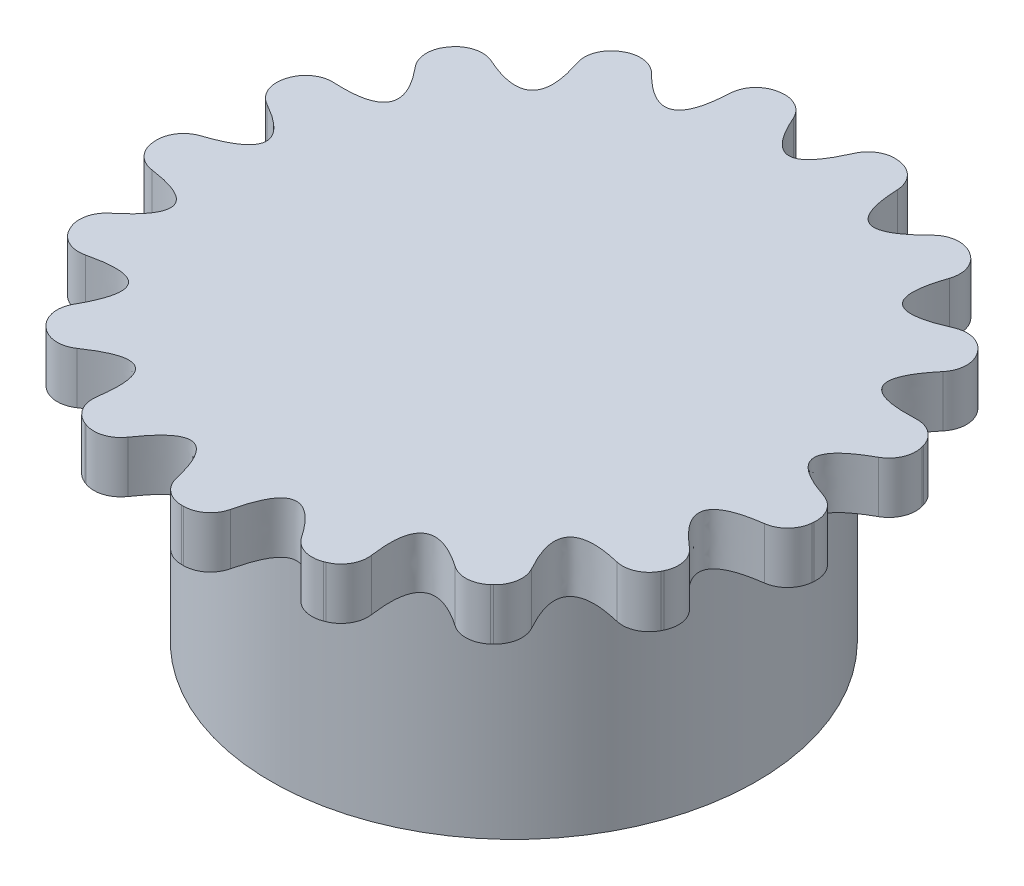
SolidWorks part; units mm, degrees
material "1023 Carbon Steel Sheet (SS)"
ref_plane "Front Plane" through (0, 0, 0) normal (0, 0, 1) x (1, 0, 0)
ref_plane "Top Plane" through (0, 0, 0) normal (0, 1, 0) x (1, 0, 0)
ref_plane "Right Plane" through (0, 0, 0) normal (1, 0, 0) x (0, 0, -1)
sketch "Sketch1" plane through (0, 0, 0) normal (0, 1, 0) x (1, 0, 0)
  circle A0 centre (0, 0) radius 13.7922
  dimension "D1" = 27.5844
extrude "Boss-Extrude1" add sketch "Sketch1" along normal blind 13.1318
sketch "Sketch2" plane through (0, 13.1318, 0) normal (0, 1, 0) x (1, 0, 0)
  circle A0 centre (0, 0) radius 18.796
  dimension "D1" = 37.592
extrude "Boss-Extrude2" add sketch "Sketch2" along normal blind 2.921
sketch "Sketch3" plane through (0, 16.0528, 0) normal (0, 1, 0) x (1, 0, 0)
  circle A0 centre (0, 0) radius 18.796 construction
  spline S0 degree 2 poles (2.1498, 18.6727) (-0.0016, 12.5689) (-2.1428, 18.6735) knots 0 0 0 1 1 1
  point P0 (0, 15.621)
  point P3 (0, 18.796)
  point P6 (0, 0)
  point P9 (3.5297, 19.0232)
  circle M1 centre (0, 0) radius 18.796
  dimension "D1" = 3.175
  dimension "D2" = 4.2926
  dimension "D3" = 2.1463
extrude "Cut-Extrude1" cut sketch "Sketch3" against normal blind 2.921 and the other way through all contours S0 M1
fillet "Fillet1" radius 1.524 2 edges at (2.1498, 14.5923, -18.6727) (-2.1428, 14.5923, -18.6735)
pattern_circular "CirPattern1" count 17 over 360 about axis through (0, 16.0528, 0) along (0, 1, 0) of "Cut-Extrude1", "Fillet1"
